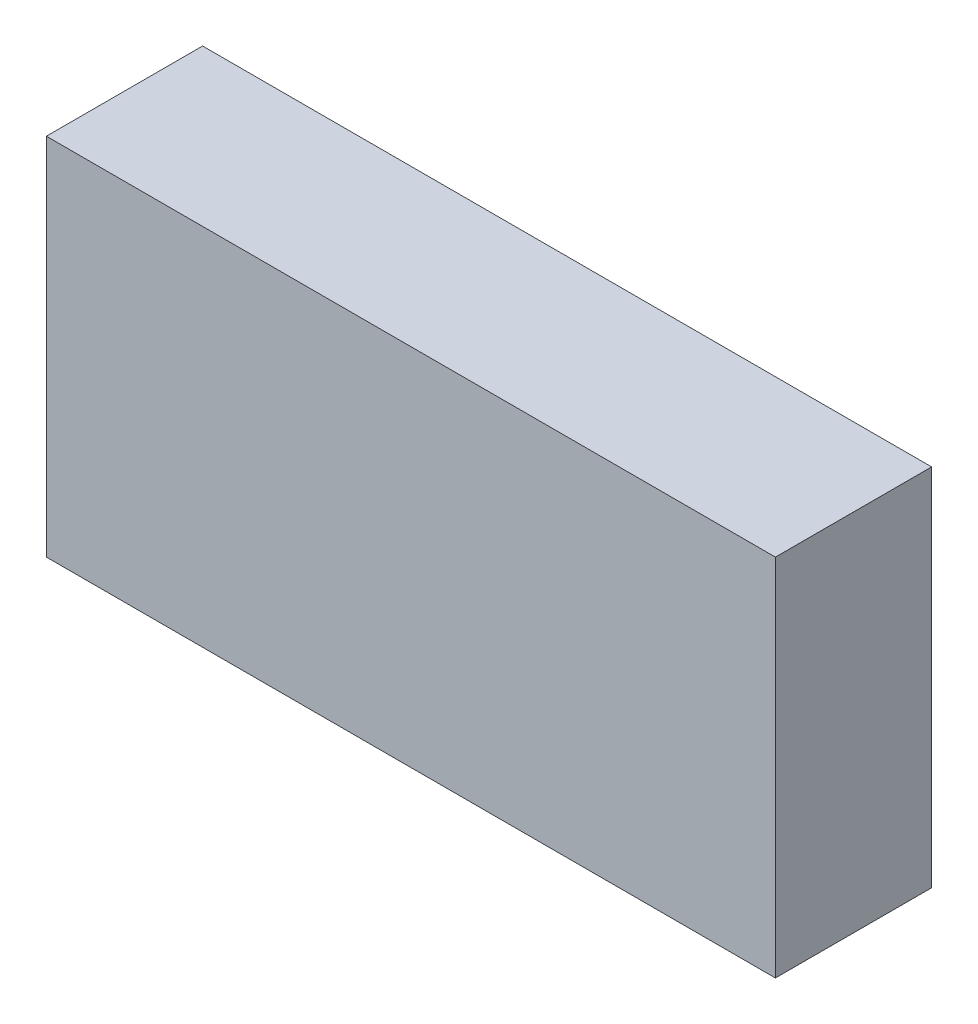
SolidWorks part; units mm, degrees
ref_plane "正面" through (0, 0, 0) normal (0, 0, 1) x (1, 0, 0)
ref_plane "平面" through (0, 0, 0) normal (0, 1, 0) x (1, 0, 0)
ref_plane "右側面" through (0, 0, 0) normal (1, 0, 0) x (0, 0, -1)
sketch "ｽｹｯﾁ1" plane through (0, 0, 0) normal (0, 0, 1) x (1, 0, 0)
  line L1 (0, 0) -> (70, 0)
  line L2 (0, 0) -> (0, 35)
  line L3 (0, 35) -> (70, 35)
  line L4 (70, 0) -> (70, 35)
extrude "ﾎﾞｽ - 押し出し1" add sketch "ｽｹｯﾁ1" along normal blind 15
